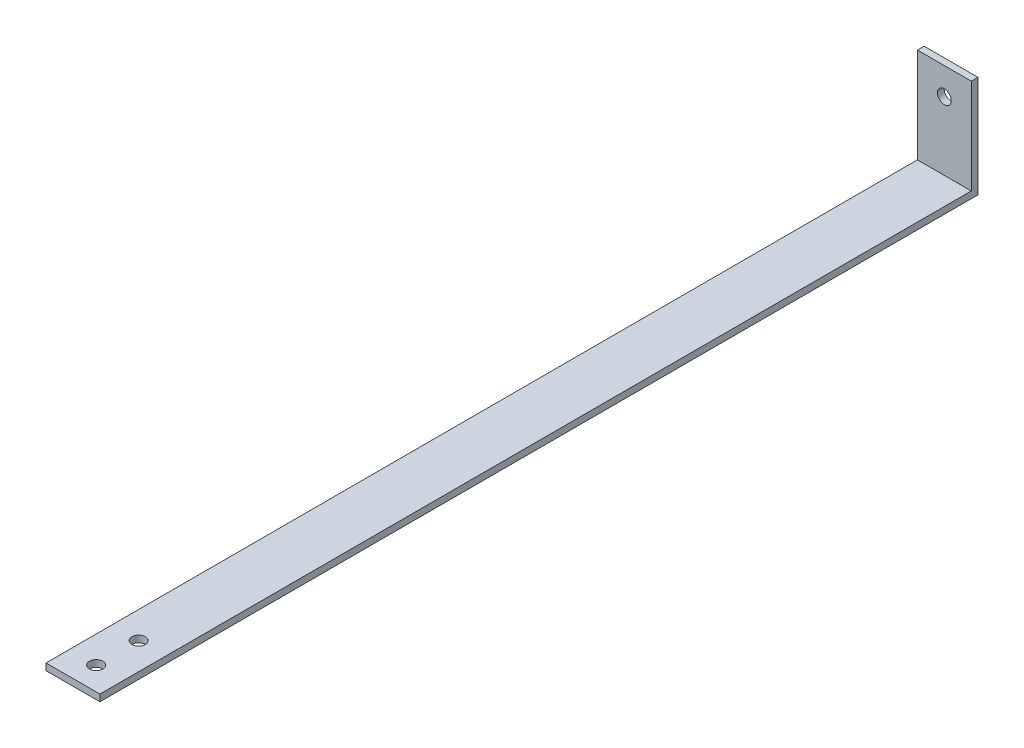
SolidWorks part; units mm, degrees
ref_plane "Alzado" through (0, 0, 0) normal (0, 0, 1) x (1, 0, 0)
ref_plane "Planta" through (0, 0, 0) normal (0, 1, 0) x (1, 0, 0)
ref_plane "Vista lateral" through (0, 0, 0) normal (1, 0, 0) x (0, 0, -1)
sketch "Croquis1" plane through (0, 0, 0) normal (1, 0, 0) x (0, 0, -1)
  line L0 (-6.31, 95.93) -> (0, 95.93)
  line L1 (0, 95.93) -> (0, 0)
  line L2 (0, 0) -> (-902.2, 0)
  line L3 (-902.2, 0) -> (-902.2, 6.31)
  line L4 (-902.2, 6.31) -> (-6.31, 6.31)
  line L5 (-6.31, 6.31) -> (-6.31, 95.93)
  dimension "D1" = 902.2
  dimension "D2" = 6.31
  dimension "D3" = 95.93
  dimension "D4" = 6.31
extrude "Saliente-Extruir1" add sketch "Croquis1" along normal blind 50.8
sketch "Croquis2" plane through (0, 0, 0) normal (0, -1, 0) x (-1, 0, 0)
  line L0 (-25.4, -902.2) -> (-25.4, -885.7) construction
  line L1 (-50.8, -902.2) -> (0, -902.2) construction
  line L2 (-25.4, -885.7) -> (-25.4, -854.7) construction
  circle A0 centre (-25.4, -885.7) radius 6.5
  circle A1 centre (-25.4, -854.7) radius 6.5
  dimension "D1" = 13
  dimension "D2" = 13
extrude "Cortar-Extruir1" cut sketch "Croquis2" against normal blind 10
sketch "Croquis3" plane through (0, 0, 0) normal (0, 0, -1) x (-1, 0, 0)
  line L0 (-25.4, 95.93) -> (-25.4, 70.53) construction
  line L1 (-50.8, 95.93) -> (0, 95.93) construction
  circle A0 centre (-25.4, 70.53) radius 6.5
  dimension "D2" = 13
  dimension "D1" = 25.4
extrude "Cortar-Extruir2" cut sketch "Croquis3" against normal blind 10
sketch "Croquis4" plane through (0, 0, 0) normal (0, -1, 0) x (1, 0, 0)
  line L0 (50.8, 902.2) -> (50.8, 827.7)
  line L1 (50.8, 902.2) -> (50.8, 0) construction
  line L2 (50.8, 827.7) -> (0, 827.7)
  line L3 (0, 902.2) -> (0, 0) construction
  line L4 (0, 827.7) -> (0, 902.2)
  line L5 (0, 902.2) -> (50.8, 902.2)
  dimension "D1" = 74.5
extrude "Cortar-Extruir3" cut sketch "Croquis4" against normal blind 10
sketch "Croquis5" plane through (0, 0, 0) normal (0, -1, 0) x (-1, 0, 0)
  circle A0 centre (-25.4, -765.81) radius 6.35
  circle A1 centre (-25.4, -805.81) radius 6.35
extrude "Cortar-Extruir4" cut sketch "Croquis5" against normal blind 10
